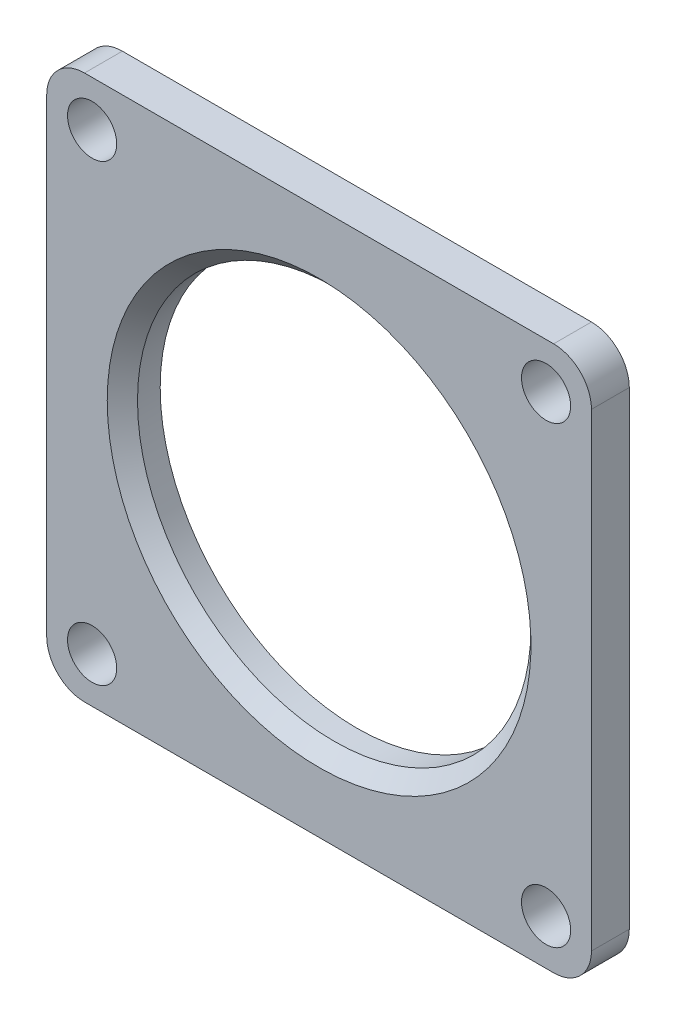
SolidWorks part; units mm, degrees
ref_plane "Front Plane" through (0, 0, 0) normal (0, 0, 1) x (1, 0, 0)
ref_plane "Top Plane" through (0, 0, 0) normal (0, 1, 0) x (1, 0, 0)
ref_plane "Right Plane" through (0, 0, 0) normal (1, 0, 0) x (0, 0, -1)
ref_plane "Plane1" through (0, 0, 0) normal (0, 0, -1) x (-1, 0, 0)
sketch "Sketch1" plane through (0, 0, 0) normal (0, 0, -1) x (-1, 0, 0)
  line L0 (0, 0) -> (0, 72)
  line L1 (0, 72) -> (-72, 72)
  line L2 (-72, 72) -> (-72, 0)
  line L3 (-72, 0) -> (0, 0)
extrude "Boss-Extrude1" add sketch "Sketch1" against normal blind 5
hole_wizard "Hole1" positions "Sketch3" profile "Sketch2" legacy
sketch "Sketch3" plane through (0, 0, 0) normal (0, 0, -1) x (-1, 0, 0)
  point P0 (-36, 36)
sketch "Sketch2" plane through (36, 36, 0) normal (1, 0, 0) x (0, 1, 0)
  line L0 (0, 0) -> (0, 2.25)
  line L1 (0, 2.25) -> (31.3, 2.25)
  line L2 (31.3, 2.25) -> (31.3, 0)
  line L3 (31.3, 0) -> (0, 0)
  line L4 (0, 110) -> (0, -10) construction
  dimension "Diameter" = 62.6
  dimension "Depth" = 2.25
ref_plane "Plane2" through (0, 36, 0) normal (0, 1, 0) x (1, 0, 0)
sketch "Sketch4" plane through (0, 36, 0) normal (0, 1, 0) x (1, 0, 0)
  line L0 (63.8, 0) -> (36, 0)
  line L1 (36, 0) -> (36, -2.25)
  line L2 (36, -2.25) -> (63.8, -2.25)
  line L3 (63.8, -2.25) -> (63.8, 0)
  line L4 (36, 0) -> (36, -2.25) construction
revolve "Revolve1" add sketch "Sketch4" angle 360 about L4
hole_wizard "Hole2" positions "Sketch6" profile "Sketch5" legacy
sketch "Sketch6" plane through (0, 0, 5) normal (0, 0, 1) x (1, 0, 0)
  point P0 (66, 6)
  point P1 (6, 6)
  point P2 (6, 66)
  point P3 (66, 66)
sketch "Sketch5" plane through (66, 6, 5) normal (1, 0, 0) x (0, -1, 0)
  line L0 (0, 0) -> (0, 5)
  line L1 (0, 5) -> (3.25, 5)
  line L2 (3.25, 5) -> (3.25, 0)
  line L3 (3.25, 0) -> (0, 0)
  line L4 (0, 110) -> (0, -10) construction
  dimension "Diameter" = 6.5
  dimension "Depth" = 5
hole_wizard "Hole3" positions "Sketch8" profile "Sketch7" legacy
sketch "Sketch8" plane through (0, 0, 5) normal (0, 0, 1) x (1, 0, 0)
  point P0 (36, 36)
sketch "Sketch7" plane through (36, 36, 5) normal (1, 0, 0) x (0, -1, 0)
  line L0 (0, 0) -> (0, 5)
  line L1 (0, 5) -> (26, 5)
  line L2 (26, 5) -> (26, 0)
  line L3 (26, 0) -> (0, 0)
  line L4 (0, 110) -> (0, -10) construction
  dimension "Diameter" = 52
  dimension "Depth" = 5
chamfer "Chamfer1" distance 2 angle 45 1 edges at (62, 36, 5)
fillet "Fillet1" radius 5 4 edges at (0, 72, 2.5) (72, 72, 2.5) (0, 0, 2.5) (72, 0, 2.5)
